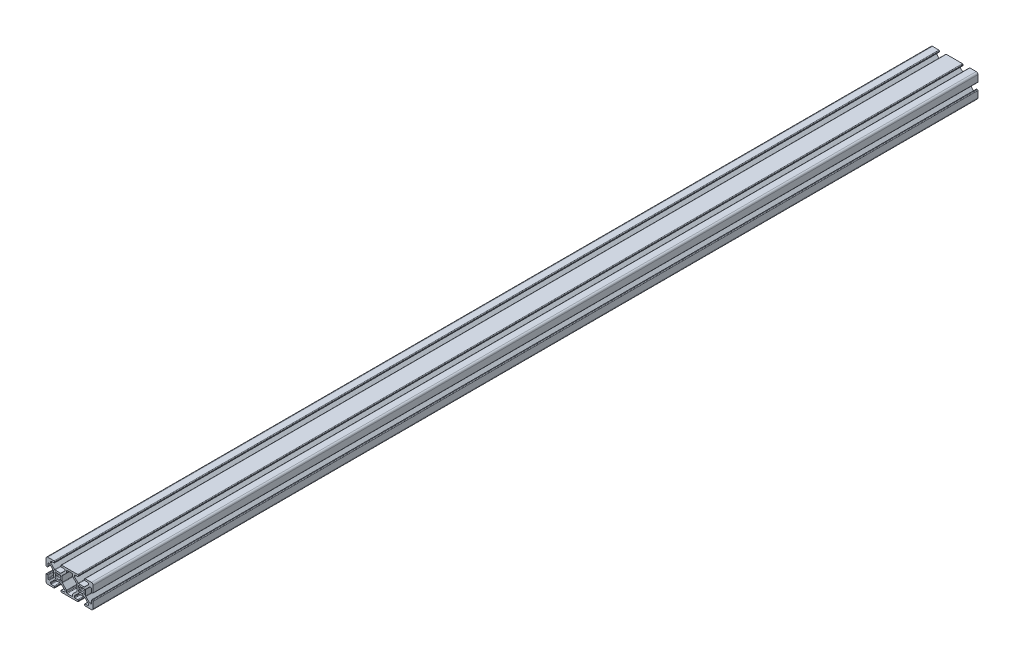
SolidWorks part; units mm, degrees
ref_plane "Front Plane" through (0, 0, 0) normal (0, 0, 1) x (1, 0, 0)
ref_plane "Top Plane" through (0, 0, 0) normal (0, 1, 0) x (1, 0, 0)
ref_plane "Right Plane" through (0, 0, 0) normal (1, 0, 0) x (0, 0, -1)
sketch "Sketch1" plane through (0, 0, 0) normal (0, 0, 1) x (1, 0, 0)
  line L0 (-16.6492, -61.9845) -> (-16.8288, -61.8049)
  line L1 (-16.8288, -57.5551) -> (-16.6492, -57.3755)
  line L2 (-12.3994, -57.3755) -> (-12.2198, -57.5551)
  line L3 (-12.2198, -61.8049) -> (-12.3994, -61.9845)
  line L4 (-27.0293, -67.672) -> (-27.0293, -66.3248)
  line L5 (-27.1781, -65.9655) -> (-30.7205, -62.4231)
  line L6 (-30.8693, -62.0639) -> (-30.8693, -57.2961)
  line L7 (-30.7205, -56.9369) -> (-27.1781, -53.3944)
  line L8 (-27.0293, -53.0352) -> (-27.0293, -51.688)
  line L9 (-26.5213, -51.18) -> (-22.5273, -51.18)
  line L10 (-22.0193, -51.688) -> (-22.0193, -53.0352)
  line L11 (-21.8705, -53.3944) -> (-18.3281, -56.9369)
  line L12 (-18.1793, -57.2961) -> (-18.1793, -62.0639)
  line L13 (-18.3281, -62.4231) -> (-21.8705, -65.9655)
  line L14 (-22.0193, -66.3248) -> (-22.0193, -67.672)
  line L15 (-22.5273, -68.18) -> (-26.5213, -68.18)
  line L16 (-36.6492, -61.9845) -> (-36.8288, -61.8049)
  line L17 (-36.8288, -57.5551) -> (-36.6492, -57.3755)
  line L18 (-32.3994, -57.3755) -> (-32.2198, -57.5551)
  line L19 (-32.2198, -61.8049) -> (-32.3994, -61.9845)
  line L20 (-36.9082, -63.335) -> (-32.1404, -63.335)
  line L21 (-31.7812, -63.4838) -> (-28.6781, -66.5869)
  line L22 (-28.5293, -66.9461) -> (-28.5293, -67.672)
  line L23 (-29.0373, -68.18) -> (-31.3863, -68.18)
  line L24 (-31.8943, -68.688) -> (-31.8943, -69.172)
  line L25 (-31.3863, -69.68) -> (-17.6623, -69.68)
  line L26 (-17.1543, -69.172) -> (-17.1543, -68.688)
  line L27 (-17.6623, -68.18) -> (-20.0113, -68.18)
  line L28 (-20.5193, -67.672) -> (-20.5193, -66.9461)
  line L29 (-20.3705, -66.5869) -> (-17.2674, -63.4838)
  line L30 (-16.9082, -63.335) -> (-12.1404, -63.335)
  line L31 (-11.7812, -63.4838) -> (-8.6781, -66.5869)
  line L32 (-8.5293, -66.9461) -> (-8.5293, -67.672)
  line L33 (-9.0373, -68.18) -> (-11.3863, -68.18)
  line L34 (-11.8943, -68.688) -> (-11.8943, -69.172)
  line L35 (-11.3863, -69.68) -> (-6.0243, -69.68)
  line L36 (-4.5243, -68.18) -> (-4.5243, -62.818)
  line L37 (-5.0323, -62.31) -> (-5.5163, -62.31)
  line L38 (-6.0243, -62.818) -> (-6.0243, -65.167)
  line L39 (-6.5323, -65.675) -> (-7.2582, -65.675)
  line L40 (-7.6174, -65.5262) -> (-10.7205, -62.4231)
  line L41 (-10.8693, -62.0639) -> (-10.8693, -57.2961)
  line L42 (-10.7205, -56.9369) -> (-7.6174, -53.8338)
  line L43 (-7.2582, -53.685) -> (-6.5323, -53.685)
  line L44 (-6.0243, -54.193) -> (-6.0243, -56.542)
  line L45 (-5.5163, -57.05) -> (-5.0323, -57.05)
  line L46 (-4.5243, -56.542) -> (-4.5243, -51.18)
  line L47 (-6.0243, -49.68) -> (-11.3863, -49.68)
  line L48 (-11.8943, -50.188) -> (-11.8943, -50.672)
  line L49 (-11.3863, -51.18) -> (-9.0373, -51.18)
  line L50 (-8.5293, -51.688) -> (-8.5293, -52.4139)
  line L51 (-8.6781, -52.7731) -> (-11.7812, -55.8762)
  line L52 (-12.1404, -56.025) -> (-16.9082, -56.025)
  line L53 (-17.2674, -55.8762) -> (-20.3705, -52.7731)
  line L54 (-20.5193, -52.4139) -> (-20.5193, -51.688)
  line L55 (-20.0113, -51.18) -> (-17.6623, -51.18)
  line L56 (-17.1543, -50.672) -> (-17.1543, -50.188)
  line L57 (-17.6623, -49.68) -> (-31.3863, -49.68)
  line L58 (-31.8943, -50.188) -> (-31.8943, -50.672)
  line L59 (-31.3863, -51.18) -> (-29.0373, -51.18)
  line L60 (-28.5293, -51.688) -> (-28.5293, -52.4139)
  line L61 (-28.6781, -52.7731) -> (-31.7812, -55.8762)
  line L62 (-32.1404, -56.025) -> (-36.9082, -56.025)
  line L63 (-37.2674, -55.8762) -> (-40.3705, -52.7731)
  line L64 (-40.5193, -52.4139) -> (-40.5193, -51.688)
  line L65 (-40.0113, -51.18) -> (-37.6623, -51.18)
  line L66 (-37.1543, -50.672) -> (-37.1543, -50.188)
  line L67 (-37.6623, -49.68) -> (-43.0243, -49.68)
  line L68 (-44.5243, -51.18) -> (-44.5243, -56.542)
  line L69 (-44.0163, -57.05) -> (-43.5323, -57.05)
  line L70 (-43.0243, -56.542) -> (-43.0243, -54.193)
  line L71 (-42.5163, -53.685) -> (-41.7904, -53.685)
  line L72 (-41.4312, -53.8338) -> (-38.3281, -56.9369)
  line L73 (-38.1793, -57.2961) -> (-38.1793, -62.0639)
  line L74 (-38.3281, -62.4231) -> (-41.4312, -65.5262)
  line L75 (-41.7904, -65.675) -> (-42.5163, -65.675)
  line L76 (-43.0243, -65.167) -> (-43.0243, -62.818)
  line L77 (-43.5323, -62.31) -> (-44.0163, -62.31)
  line L78 (-44.5243, -62.818) -> (-44.5243, -68.18)
  line L79 (-43.0243, -69.68) -> (-37.6623, -69.68)
  line L80 (-37.1543, -69.172) -> (-37.1543, -68.688)
  line L81 (-37.6623, -68.18) -> (-40.0113, -68.18)
  line L82 (-40.5193, -67.672) -> (-40.5193, -66.9461)
  line L83 (-40.3705, -66.5869) -> (-37.2674, -63.4838)
  arc A0 (-16.4594, -60.484) -> (-16.8288, -61.8049) centre (-16.2723, -61.2484) ccw
  arc A1 (-16.4594, -58.876) -> (-16.4594, -60.484) centre (-14.5243, -59.68) ccw
  arc A2 (-16.8288, -57.5551) -> (-16.4594, -58.876) centre (-16.2723, -58.1116) ccw
  arc A3 (-15.3283, -57.7449) -> (-16.6492, -57.3755) centre (-16.0927, -57.932) ccw
  arc A4 (-13.7203, -57.7449) -> (-15.3283, -57.7449) centre (-14.5243, -59.68) ccw
  arc A5 (-12.3994, -57.3755) -> (-13.7203, -57.7449) centre (-12.9559, -57.932) ccw
  arc A6 (-12.5892, -58.876) -> (-12.2198, -57.5551) centre (-12.7763, -58.1116) ccw
  arc A7 (-12.5892, -60.484) -> (-12.5892, -58.876) centre (-14.5243, -59.68) ccw
  arc A8 (-12.2198, -61.8049) -> (-12.5892, -60.484) centre (-12.7763, -61.2484) ccw
  arc A9 (-13.7203, -61.6151) -> (-12.3994, -61.9845) centre (-12.9559, -61.428) ccw
  arc A10 (-15.3283, -61.6151) -> (-13.7203, -61.6151) centre (-14.5243, -59.68) ccw
  arc A11 (-16.6492, -61.9845) -> (-15.3283, -61.6151) centre (-16.0927, -61.428) ccw
  arc A12 (-27.0293, -67.672) -> (-26.5213, -68.18) centre (-26.5213, -67.672) ccw
  arc A13 (-27.0293, -66.3248) -> (-27.1781, -65.9655) centre (-27.5373, -66.3248) ccw
  arc A14 (-30.8693, -62.0639) -> (-30.7205, -62.4231) centre (-30.3613, -62.0639) ccw
  arc A15 (-30.7205, -56.9369) -> (-30.8693, -57.2961) centre (-30.3613, -57.2961) ccw
  arc A16 (-27.1781, -53.3944) -> (-27.0293, -53.0352) centre (-27.5373, -53.0352) ccw
  arc A17 (-26.5213, -51.18) -> (-27.0293, -51.688) centre (-26.5213, -51.688) ccw
  arc A18 (-22.0193, -51.688) -> (-22.5273, -51.18) centre (-22.5273, -51.688) ccw
  arc A19 (-22.0193, -53.0352) -> (-21.8705, -53.3944) centre (-21.5113, -53.0352) ccw
  arc A20 (-18.1793, -57.2961) -> (-18.3281, -56.9369) centre (-18.6873, -57.2961) ccw
  arc A21 (-18.3281, -62.4231) -> (-18.1793, -62.0639) centre (-18.6873, -62.0639) ccw
  arc A22 (-21.8705, -65.9655) -> (-22.0193, -66.3248) centre (-21.5113, -66.3248) ccw
  arc A23 (-22.5273, -68.18) -> (-22.0193, -67.672) centre (-22.5273, -67.672) ccw
  arc A24 (-36.4594, -60.484) -> (-36.8288, -61.8049) centre (-36.2723, -61.2484) ccw
  arc A25 (-36.4594, -58.876) -> (-36.4594, -60.484) centre (-34.5243, -59.68) ccw
  arc A26 (-36.8288, -57.5551) -> (-36.4594, -58.876) centre (-36.2723, -58.1116) ccw
  arc A27 (-35.3283, -57.7449) -> (-36.6492, -57.3755) centre (-36.0927, -57.932) ccw
  arc A28 (-33.7203, -57.7449) -> (-35.3283, -57.7449) centre (-34.5243, -59.68) ccw
  arc A29 (-32.3994, -57.3755) -> (-33.7203, -57.7449) centre (-32.9559, -57.932) ccw
  arc A30 (-32.5892, -58.876) -> (-32.2198, -57.5551) centre (-32.7763, -58.1116) ccw
  arc A31 (-32.5892, -60.484) -> (-32.5892, -58.876) centre (-34.5243, -59.68) ccw
  arc A32 (-32.2198, -61.8049) -> (-32.5892, -60.484) centre (-32.7763, -61.2484) ccw
  arc A33 (-33.7203, -61.6151) -> (-32.3994, -61.9845) centre (-32.9559, -61.428) ccw
  arc A34 (-35.3283, -61.6151) -> (-33.7203, -61.6151) centre (-34.5243, -59.68) ccw
  arc A35 (-36.6492, -61.9845) -> (-35.3283, -61.6151) centre (-36.0927, -61.428) ccw
  arc A36 (-36.9082, -63.335) -> (-37.2674, -63.4838) centre (-36.9082, -63.843) ccw
  arc A37 (-31.7812, -63.4838) -> (-32.1404, -63.335) centre (-32.1404, -63.843) ccw
  arc A38 (-28.5293, -66.9461) -> (-28.6781, -66.5869) centre (-29.0373, -66.9461) ccw
  arc A39 (-29.0373, -68.18) -> (-28.5293, -67.672) centre (-29.0373, -67.672) ccw
  arc A40 (-31.3863, -68.18) -> (-31.8943, -68.688) centre (-31.3863, -68.688) ccw
  arc A41 (-31.8943, -69.172) -> (-31.3863, -69.68) centre (-31.3863, -69.172) ccw
  arc A42 (-17.6623, -69.68) -> (-17.1543, -69.172) centre (-17.6623, -69.172) ccw
  arc A43 (-17.1543, -68.688) -> (-17.6623, -68.18) centre (-17.6623, -68.688) ccw
  arc A44 (-20.5193, -67.672) -> (-20.0113, -68.18) centre (-20.0113, -67.672) ccw
  arc A45 (-20.3705, -66.5869) -> (-20.5193, -66.9461) centre (-20.0113, -66.9461) ccw
  arc A46 (-16.9082, -63.335) -> (-17.2674, -63.4838) centre (-16.9082, -63.843) ccw
  arc A47 (-11.7812, -63.4838) -> (-12.1404, -63.335) centre (-12.1404, -63.843) ccw
  arc A48 (-8.5293, -66.9461) -> (-8.6781, -66.5869) centre (-9.0373, -66.9461) ccw
  arc A49 (-9.0373, -68.18) -> (-8.5293, -67.672) centre (-9.0373, -67.672) ccw
  arc A50 (-11.3863, -68.18) -> (-11.8943, -68.688) centre (-11.3863, -68.688) ccw
  arc A51 (-11.8943, -69.172) -> (-11.3863, -69.68) centre (-11.3863, -69.172) ccw
  arc A52 (-6.0243, -69.68) -> (-4.5243, -68.18) centre (-6.0243, -68.18) ccw
  arc A53 (-4.5243, -62.818) -> (-5.0323, -62.31) centre (-5.0323, -62.818) ccw
  arc A54 (-5.5163, -62.31) -> (-6.0243, -62.818) centre (-5.5163, -62.818) ccw
  arc A55 (-6.5323, -65.675) -> (-6.0243, -65.167) centre (-6.5323, -65.167) ccw
  arc A56 (-7.6174, -65.5262) -> (-7.2582, -65.675) centre (-7.2582, -65.167) ccw
  arc A57 (-10.8693, -62.0639) -> (-10.7205, -62.4231) centre (-10.3613, -62.0639) ccw
  arc A58 (-10.7205, -56.9369) -> (-10.8693, -57.2961) centre (-10.3613, -57.2961) ccw
  arc A59 (-7.2582, -53.685) -> (-7.6174, -53.8338) centre (-7.2582, -54.193) ccw
  arc A60 (-6.0243, -54.193) -> (-6.5323, -53.685) centre (-6.5323, -54.193) ccw
  arc A61 (-6.0243, -56.542) -> (-5.5163, -57.05) centre (-5.5163, -56.542) ccw
  arc A62 (-5.0323, -57.05) -> (-4.5243, -56.542) centre (-5.0323, -56.542) ccw
  arc A63 (-4.5243, -51.18) -> (-6.0243, -49.68) centre (-6.0243, -51.18) ccw
  arc A64 (-11.3863, -49.68) -> (-11.8943, -50.188) centre (-11.3863, -50.188) ccw
  arc A65 (-11.8943, -50.672) -> (-11.3863, -51.18) centre (-11.3863, -50.672) ccw
  arc A66 (-8.5293, -51.688) -> (-9.0373, -51.18) centre (-9.0373, -51.688) ccw
  arc A67 (-8.6781, -52.7731) -> (-8.5293, -52.4139) centre (-9.0373, -52.4139) ccw
  arc A68 (-12.1404, -56.025) -> (-11.7812, -55.8762) centre (-12.1404, -55.517) ccw
  arc A69 (-17.2674, -55.8762) -> (-16.9082, -56.025) centre (-16.9082, -55.517) ccw
  arc A70 (-20.5193, -52.4139) -> (-20.3705, -52.7731) centre (-20.0113, -52.4139) ccw
  arc A71 (-20.0113, -51.18) -> (-20.5193, -51.688) centre (-20.0113, -51.688) ccw
  arc A72 (-17.6623, -51.18) -> (-17.1543, -50.672) centre (-17.6623, -50.672) ccw
  arc A73 (-17.1543, -50.188) -> (-17.6623, -49.68) centre (-17.6623, -50.188) ccw
  arc A74 (-31.3863, -49.68) -> (-31.8943, -50.188) centre (-31.3863, -50.188) ccw
  arc A75 (-31.8943, -50.672) -> (-31.3863, -51.18) centre (-31.3863, -50.672) ccw
  arc A76 (-28.5293, -51.688) -> (-29.0373, -51.18) centre (-29.0373, -51.688) ccw
  arc A77 (-28.6781, -52.7731) -> (-28.5293, -52.4139) centre (-29.0373, -52.4139) ccw
  arc A78 (-32.1404, -56.025) -> (-31.7812, -55.8762) centre (-32.1404, -55.517) ccw
  arc A79 (-37.2674, -55.8762) -> (-36.9082, -56.025) centre (-36.9082, -55.517) ccw
  arc A80 (-40.5193, -52.4139) -> (-40.3705, -52.7731) centre (-40.0113, -52.4139) ccw
  arc A81 (-40.0113, -51.18) -> (-40.5193, -51.688) centre (-40.0113, -51.688) ccw
  arc A82 (-37.6623, -51.18) -> (-37.1543, -50.672) centre (-37.6623, -50.672) ccw
  arc A83 (-37.1543, -50.188) -> (-37.6623, -49.68) centre (-37.6623, -50.188) ccw
  arc A84 (-43.0243, -49.68) -> (-44.5243, -51.18) centre (-43.0243, -51.18) ccw
  arc A85 (-44.5243, -56.542) -> (-44.0163, -57.05) centre (-44.0163, -56.542) ccw
  arc A86 (-43.5323, -57.05) -> (-43.0243, -56.542) centre (-43.5323, -56.542) ccw
  arc A87 (-42.5163, -53.685) -> (-43.0243, -54.193) centre (-42.5163, -54.193) ccw
  arc A88 (-41.4312, -53.8338) -> (-41.7904, -53.685) centre (-41.7904, -54.193) ccw
  arc A89 (-38.1793, -57.2961) -> (-38.3281, -56.9369) centre (-38.6873, -57.2961) ccw
  arc A90 (-38.3281, -62.4231) -> (-38.1793, -62.0639) centre (-38.6873, -62.0639) ccw
  arc A91 (-41.7904, -65.675) -> (-41.4312, -65.5262) centre (-41.7904, -65.167) ccw
  arc A92 (-43.0243, -65.167) -> (-42.5163, -65.675) centre (-42.5163, -65.167) ccw
  arc A93 (-43.0243, -62.818) -> (-43.5323, -62.31) centre (-43.5323, -62.818) ccw
  arc A94 (-44.0163, -62.31) -> (-44.5243, -62.818) centre (-44.0163, -62.818) ccw
  arc A95 (-44.5243, -68.18) -> (-43.0243, -69.68) centre (-43.0243, -68.18) ccw
  arc A96 (-37.6623, -69.68) -> (-37.1543, -69.172) centre (-37.6623, -69.172) ccw
  arc A97 (-37.1543, -68.688) -> (-37.6623, -68.18) centre (-37.6623, -68.688) ccw
  arc A98 (-40.5193, -67.672) -> (-40.0113, -68.18) centre (-40.0113, -67.672) ccw
  arc A99 (-40.3705, -66.5869) -> (-40.5193, -66.9461) centre (-40.0113, -66.9461) ccw
extrude "Extrude1" add sketch "Sketch1" along normal blind 750
